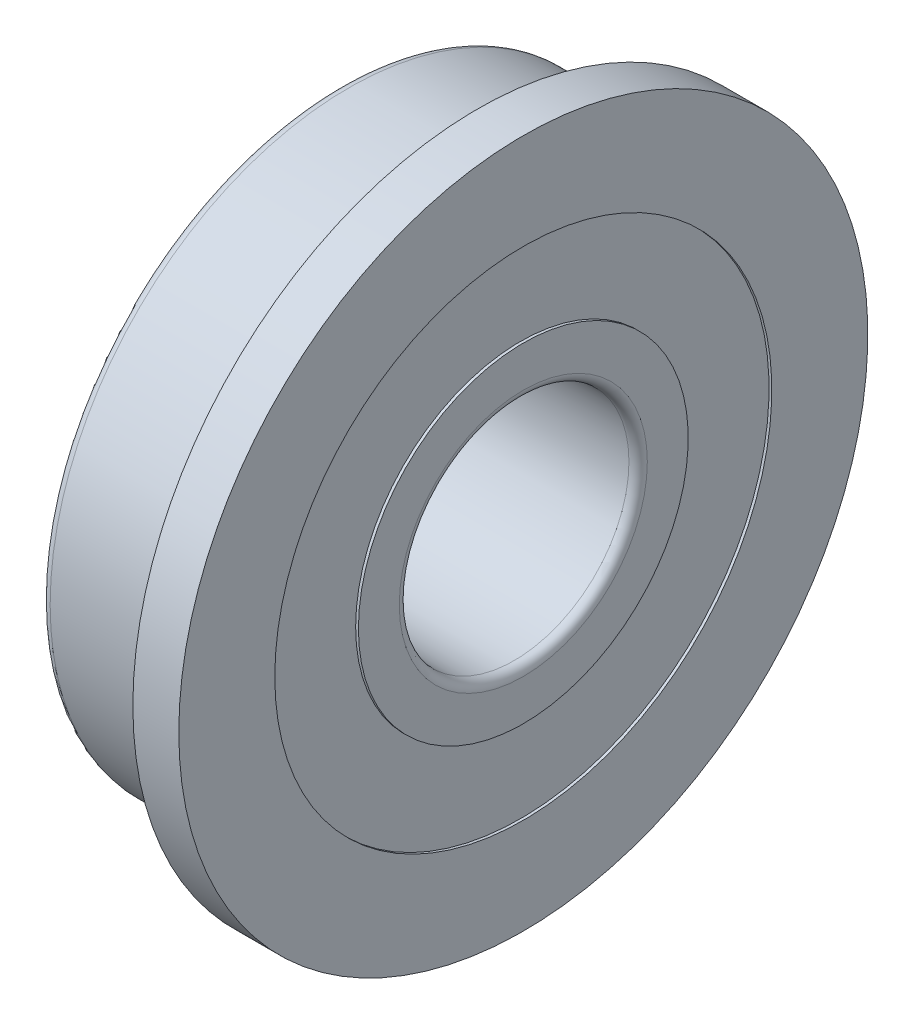
SolidWorks part; units mm, degrees
ref_plane "前视基准面" through (0, 0, 0) normal (0, 0, 1) x (1, 0, 0)
ref_plane "上视基准面" through (0, 0, 0) normal (0, 1, 0) x (1, 0, 0)
ref_plane "右视基准面" through (0, 0, 0) normal (1, 0, 0) x (0, 0, -1)
sketch "尺寸草图" plane through (0, 0, 0) normal (0, 0, 1) x (1, 0, 0)
  line L0 (0, 2.5) -> (0, 11.3472) construction
  line L1 (0, 0) -> (3.4534, 0) construction
  line L2 (0.2, 6.5) -> (3, 6.5)
  line L3 (0, 6.3) -> (0, 2.7)
  line L4 (3, 6.5) -> (3, 7.5)
  line L5 (3, 7.5) -> (4, 7.5)
  line L6 (4, 7.5) -> (4, 2.7)
  line L7 (3, -7.5) -> (4, -7.5)
  line L8 (3, -6.5) -> (3, -7.5)
  line L9 (0.2, -6.5) -> (3, -6.5)
  line L10 (0.2, 2.5) -> (3.8, 2.5)
  line L11 (0.2, -2.5) -> (3.8, -2.5)
  line L12 (0, -2.7) -> (0, -6.3)
  line L13 (4, -2.7) -> (4, -7.5)
  line L14 (0, 2.5) -> (0, 0) construction
  line L15 (0, 4.5) -> (4, 4.5) construction
  line L16 (0, 5.2) -> (4, 5.2)
  line L17 (0, 3.8) -> (4, 3.8)
  line L18 (4, 5.41) -> (3.7, 5.41)
  line L19 (3.7, 5.41) -> (3.7, 3.59)
  line L20 (4, 3.59) -> (3.7, 3.59)
  arc A0 (0, -6.3) -> (0.2, -6.5) centre (0.2, -6.3) ccw
  arc A1 (3.8, -2.5) -> (4, -2.7) centre (3.8, -2.7) cw
  arc A2 (0, -2.7) -> (0.2, -2.5) centre (0.2, -2.7) cw
  arc A3 (3.8, 2.5) -> (4, 2.7) centre (3.8, 2.7) ccw
  arc A4 (0.2, 2.5) -> (0, 2.7) centre (0.2, 2.7) cw
  arc A5 (0, 6.3) -> (0.2, 6.5) centre (0.2, 6.3) cw
  circle A6 centre (2, 4.5) radius 1
  point P18 (0, -6.5)
  point P21 (4, -2.5)
  point P24 (0, -2.5)
  point P27 (4, 2.5)
  point P33 (0, 6.5)
  point P47 (3.7, 4.5)
  dimension "r" = 0.2
  dimension "D2" = 2
  dimension "D1" = 15
  dimension "D" = 13
  dimension "d_" = 5
  dimension "B" = 4
  dimension "C1" = 1
  dimension "D3" = 1.4
  dimension "D4" = 0.3
  dimension "D5" = 1.82
sketch "草图2" plane through (0, 0, 0) normal (0, 0, 1) x (1, 0, 0)
  line L6 (0.2, 6.5) -> (3, 6.5) construction
  line L7 (3, 6.5) -> (3, 7.5) construction
  line L8 (3, 7.5) -> (4, 7.5) construction
  line L9 (4, 7.5) -> (4, 2.7) construction
  line L10 (0.2, 2.5) -> (3.8, 2.5) construction
  line L11 (0, 6.3) -> (0, 2.7) construction
  line L14 (0, 0) -> (9.0339, 0) construction
  line L20 (0.2, 6.5) -> (3, 6.5)
  line L21 (3, 6.5) -> (3, 7.5)
  line L22 (3, 7.5) -> (4, 7.5)
  line L23 (4, 7.5) -> (4, 2.7)
  line L24 (0.2, 2.5) -> (3.8, 2.5)
  line L25 (0, 6.3) -> (0, 2.7)
  arc A4 (3.8, 2.5) -> (4, 2.7) centre (3.8, 2.7) ccw construction
  arc A5 (0, 2.7) -> (0.2, 2.5) centre (0.2, 2.7) ccw construction
  arc A6 (0.2, 6.5) -> (0, 6.3) centre (0.2, 6.3) ccw construction
  arc A11 (3.8, 2.5) -> (4, 2.7) centre (3.8, 2.7) ccw
  arc A12 (0, 2.7) -> (0.2, 2.5) centre (0.2, 2.7) ccw
  arc A13 (0.2, 6.5) -> (0, 6.3) centre (0.2, 6.3) ccw
revolve "旋转1" add sketch "草图2" angle 360 about L14
sketch "草图3" plane through (0, 0, 0) normal (0, 0, 1) x (1, 0, 0)
  line L9 (4, 7.5) -> (4, 2.7) construction
  line L11 (0, 6.3) -> (0, 2.7) construction
  line L12 (0, 3.8) -> (4, 3.8) construction
  line L13 (0, 5.2) -> (4, 5.2) construction
  line L14 (0, 0) -> (-4.8339, 0) construction
  line L15 (2.7141, 5.2) -> (4, 5.2)
  line L16 (2.7141, 3.8) -> (4, 3.8)
  line L23 (4, 5.2) -> (4, 3.8)
  line L25 (0, 5.2) -> (0, 3.8)
  line L26 (0, 3.8) -> (1.2859, 3.8)
  line L27 (0, 5.2) -> (1.2859, 5.2)
  circle A3 centre (2, 4.5) radius 1 construction
  arc A7 (2.7141, 5.2) -> (1.2859, 5.2) centre (2, 4.5) ccw
  arc A10 (1.2859, 3.8) -> (2.7141, 3.8) centre (2, 4.5) ccw
revolve "切除-旋转1" cut sketch "草图3" angle 360 about L14
sketch "草图4" plane through (0, 0, 0) normal (0, 0, 1) x (1, 0, 0)
  line L0 (2, 4.5) -> (3.0821, 4.5) construction
  line L1 (1, 4.5) -> (3, 4.5)
  circle A0 centre (2, 4.5) radius 1 construction
  arc A1 (3, 4.5) -> (1, 4.5) centre (2, 4.5) ccw
revolve "旋转2" add sketch "草图4" angle 360 about L0
pattern_circular "阵列(圆周)1" count 11 over 360 about axis through (0, 0, 0) along (1, 0, 0) of bodies 104
sketch "草图5" plane through (0, 0, 0) normal (0, 0, 1) x (1, 0, 0)
  line L0 (0, 0) -> (5.0176, 0) construction
  line L1 (3.7, 5.41) -> (3.7, 3.59) construction
  line L2 (4, 5.41) -> (3.7, 5.41) construction
  line L3 (4, 3.59) -> (3.7, 3.59) construction
  line L4 (3.7, 5.41) -> (3.7, 3.59)
  line L5 (4, 5.41) -> (3.7, 5.41)
  line L6 (4, 3.59) -> (3.7, 3.59)
  line L7 (4, 5.41) -> (4, 3.59)
  line L8 (2, 4.5) -> (2, 5.6194) construction
  line L9 (0, 5.41) -> (0, 3.59)
  line L10 (0, 3.59) -> (0.3, 3.59)
  line L11 (0, 5.41) -> (0.3, 5.41)
  line L12 (0.3, 5.41) -> (0.3, 3.59)
revolve "切除-旋转2" cut sketch "草图5" angle 360 about L0
sketch "草图6" plane through (0, 0, 0) normal (0, 0, 1) x (1, 0, 0)
  line L0 (0, 0) -> (13.587, 0) construction
  line L1 (3.7, 5.41) -> (3.94, 5.41)
  line L2 (2, 4.5) -> (2, 5.8302) construction
  line L3 (3.94, 5.41) -> (3.94, 3.59)
  line L4 (4, 3.59) -> (3.7, 3.59) construction
  line L5 (3.94, 3.59) -> (3.7, 3.59)
  line L6 (3.7, 3.59) -> (3.7, 5.41)
  line L7 (0.3, 3.59) -> (0.3, 5.41)
  line L8 (0.06, 3.59) -> (0.3, 3.59)
  line L9 (0.06, 5.41) -> (0.06, 3.59)
  line L10 (0.3, 5.41) -> (0.06, 5.41)
  dimension "D1" = 0.24
revolve "旋转3" add sketch "草图6" angle 360 about L0
